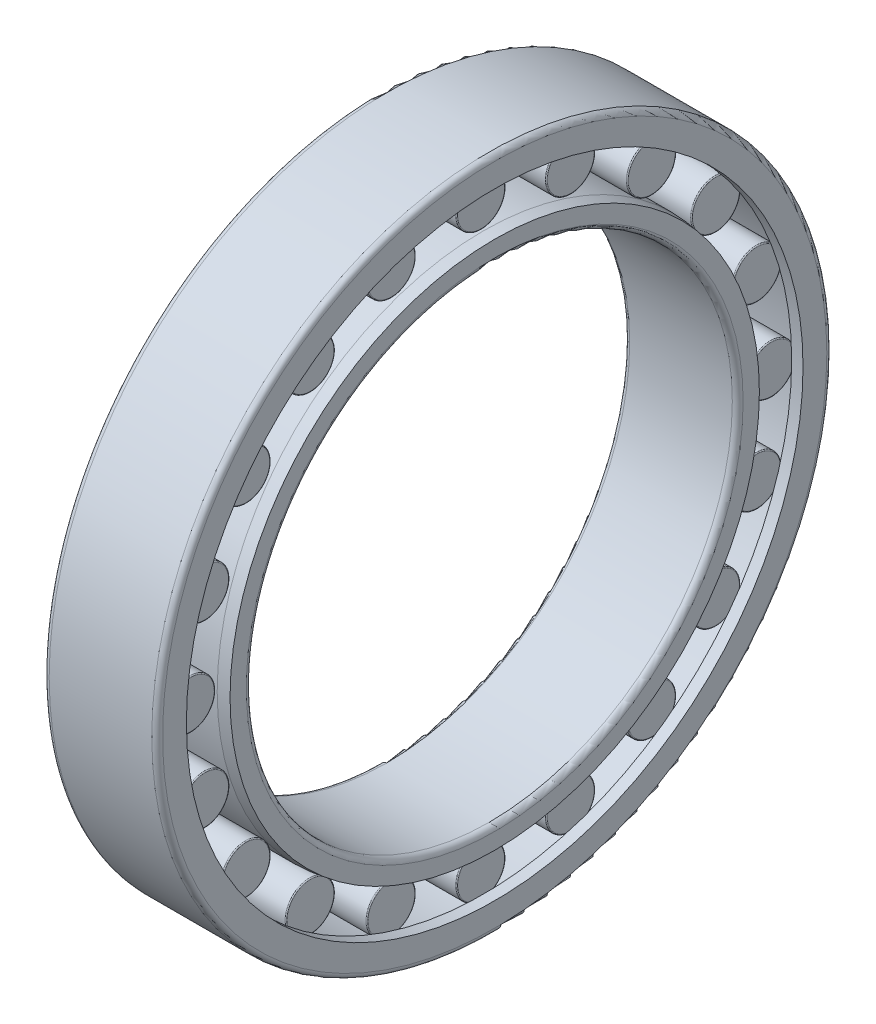
SolidWorks part; units mm, degrees
ref_plane "Plane1" through (0, 0, 0) normal (0, 0, 1) x (1, 0, 0)
ref_plane "Plane2" through (0, 0, 0) normal (0, 1, 0) x (1, 0, 0)
ref_plane "Plane3" through (0, 0, 0) normal (1, 0, 0) x (0, 0, -1)
sketch "Clipboard" plane through (0, 0, 0) normal (0, 0, 1) x (1, 0, 0)
  line L0 (-10, 0) -> (10, 0) construction
  line L1 (0, 0) -> (185.2698, -67.4327)
  line L2 (0, 0) -> (101.017, 36.7672)
  line L3 (0, 0) -> (218.798, -79.636)
  line L4 (0, 0) -> (-22.3471, -0.7804)
  dimension "CLdia" = 107.5
  dimension "Count" = 20
  dimension "Show_count" = 20
  dimension "Max_count" = 20
  dimension "Min_count" = 2
  dimension "Race_OD" = 232.84
  dimension "Race_ID" = 197.16
sketch "OutRacSke" plane through (0, 0, 0) normal (0, 0, 1) x (1, 0, 0)
  line L0 (-16.8, 114.1887) -> (-21, 114.1887)
  line L1 (-21, 114.1887) -> (-21, 123)
  line L2 (-19, 125) -> (19, 125)
  line L3 (21, 123) -> (21, 114.1888)
  line L4 (21, 114.1888) -> (16.8, 114.1888)
  line L5 (16.8, 114.1888) -> (16.8, 116.42)
  line L6 (16.8, 116.42) -> (-16.8, 116.42)
  line L7 (-16.8, 116.42) -> (-16.8, 114.1887)
  line L8 (-90, 0) -> (90, 0) construction
  arc A0 (-21, 123) -> (-19, 125) centre (-19, 123) cw
  arc A1 (19, 125) -> (21, 123) centre (19, 123) cw
  dimension "Race_OD" = 232.84
  dimension "radius" = 2
  dimension "OD" = 250
  dimension "Cyl_Len" = 33.6
  dimension "halfCylLen" = 16.8
  dimension "Width" = 42
  dimension "halfWidth" = 21
  dimension "groove_dp" = 2.2313
revolve "OuterRace" add sketch "OutRacSke" angle 360 about L8
sketch "RolDetSke" plane through (0, 0, 0) normal (0, 0, 1) x (1, 0, 0)
  line L0 (-15.96, 116.1851) -> (-15.96, 107.5)
  line L1 (-15.96, 107.5) -> (15.96, 107.5)
  line L2 (15.96, 107.5) -> (15.96, 116.1851)
  line L3 (15.5981, 116.547) -> (-15.5981, 116.547)
  line L4 (-33.6, 107.5) -> (33.6, 107.5) construction
  arc A0 (15.96, 116.1851) -> (15.5981, 116.547) centre (15.5981, 116.1851) ccw
  arc A1 (-15.5981, 116.547) -> (-15.96, 116.1851) centre (-15.5981, 116.1851) ccw
  dimension "radius" = 0.3619
  dimension "RolCLRad" = 107.5
  dimension "Length" = 31.92
  dimension "halfLength" = 15.96
  dimension "Roller_diameter" = 18.094
revolve "RollerDetailed" add sketch "RolDetSke" angle 360 about L4
ref_axis "Axis1" through (-50, 0, 0) along (1, 0, 0)
sketch "RolSimSke" plane through (0, 101.6, 0) normal (0, 0, 1) x (1, 0, 0)
  line L0 (-15.96, 14.5851) -> (-15.96, -2.7851)
  line L1 (25.4, -101.6) -> (-25.4, -101.6) construction
  line L2 (15.96, -2.7851) -> (15.96, 14.5851)
  line L3 (15.5981, 14.947) -> (-15.5981, 14.947)
  line L5 (15.5981, -3.147) -> (-15.5981, -3.147)
  arc A0 (15.96, 14.5851) -> (15.5981, 14.947) centre (15.5981, 14.5851) ccw
  arc A1 (-15.5981, 14.947) -> (-15.96, 14.5851) centre (-15.5981, 14.5851) ccw
  arc A2 (15.96, -2.7851) -> (15.5981, -3.147) centre (15.5981, -2.7851) cw
  arc A3 (-15.5981, -3.147) -> (-15.96, -2.7851) centre (-15.5981, -2.7851) cw
  dimension "radius" = 0.3619
  dimension "halfLength" = 15.96
  dimension "Roller_diameter" = 18.094
  dimension "D1" = 98.453
  dimension "Rol_Length" = 31.92
revolve "RollersSimplified" [suppressed] add sketch "RolSimSke" angle 360 about L1
sketch "InsRacSke" plane through (0, 0, 0) normal (0, 0, 1) x (1, 0, 0)
  line L0 (-16.8, 98.58) -> (-21, 98.0222)
  line L1 (-21, 98.0222) -> (-21, 92)
  line L2 (-19, 90) -> (19, 90)
  line L3 (21, 92) -> (21, 98.0222)
  line L4 (21, 98.0222) -> (16.8, 98.58)
  line L5 (16.8, 98.58) -> (-16.8, 98.58)
  line L6 (-90, 0) -> (90, 0) construction
  arc A0 (-21, 92) -> (-19, 90) centre (-19, 92) ccw
  arc A1 (19, 90) -> (21, 92) centre (19, 92) ccw
  dimension "Race_ID" = 197.16
  dimension "radius" = 2
  dimension "Cyl_Len" = 33.6
  dimension "halfWidth" = 21
  dimension "Bore" = 180
  dimension "Width" = 42
  dimension "groove_dp" = 0.5578
revolve "InnerRace" add sketch "InsRacSke" angle 360 about L6
pattern_circular "RollersDetailed" count 20 every 18 about axis through (-50, 0, 0) along (1, 0, 0) of "RollerDetailed"
sketch "CagSpiSke" plane through (0, 0, 0) normal (0, 0, 1) x (1, 0, 0)
  line L0 (18.9, 105.2383) -> (18.9, 109.7618)
  line L1 (18.9, 109.7618) -> (-18.9, 109.7618)
  line L2 (-18.9, 109.7618) -> (-18.9, 105.2383)
  line L3 (-18.9, 105.2383) -> (18.9, 105.2383)
  line L4 (-90, 0) -> (90, 0) construction
  dimension "Cag_IR" = 210.4765
  dimension "thickness" = 4.5235
  dimension "width" = 37.8
  dimension "halfwidth" = 18.9
revolve "CageSpine" [suppressed] add sketch "CagSpiSke" angle 360 about L4
equation "\"CLdia@Clipboard\" =  ( \"Race_OD@Clipboard\" + \"Race_ID@Clipboard\" )  / 4"
equation "\"Race_OD@OutRacSke\" = \"Race_OD@Clipboard\""
equation "\"halfCylLen@OutRacSke\" = \"Cyl_Len@OutRacSke\" / 2"
equation "\"RolCLRad@RolDetSke\" = \"CLdia@Clipboard\""
equation "\"Roller_diameter@RolDetSke\" =  ( \"Race_OD@Clipboard\" - \"Race_ID@Clipboard\" )  / 2 + .01"
equation "\"Roller_diameter@RolSimSke\" =  ( \"Race_OD@Clipboard\" - \"Race_ID@Clipboard\" )  / 2 + .01"
equation "\"radius@RolDetSke\" = \"Roller_diameter@RolDetSke\" / 50"
equation "\"Length@RolDetSke\" = \"Cyl_Len@OutRacSke\" * .95"
equation "\"halfLength@RolDetSke\" = \"Length@RolDetSke\" / 2"
equation "\"thickness@CagSpiSke\"  = \"Roller_diameter@RolDetSke\" * .25"
equation "\"Cag_IR@CagSpiSke\" =  \"RolCLRad@RolDetSke\" * 2 - \"thickness@CagSpiSke\""
equation "\"Rol_Length@RolSimSke\" = \"Cyl_Len@InsRacSke\" * .95"
equation "\"halfLength@RolSimSke\" = \"Rol_Length@RolSimSke\" / 2"
equation "\"radius@RolSimSke\" = \"radius@RolDetSke\""
equation "\"D1@RolSimSke\" = \"CLdia@Clipboard\" -  ( \"Roller_diameter@RolSimSke\" / 2 ) "
equation "\"Max_count@Clipboard\" = int( 3.14159265 / atn(( \"Roller_diameter@RolDetSke\" / 2) / sqr( \"RolCLRad@RolDetSke\"  *  \"RolCLRad@RolDetSke\" - ( \"Roller_diameter@RolDetSke\" / 2) *  ( \"Roller_diameter@RolDetSke\" / 2))))"
equation "\"Max_count@Clipboard\" = ((sgn( \"Max_count@Clipboard\" - \"Count@Clipboard\" )-1)*( \"Max_count@Clipboard\" - \"Count@Clipboard\" ))/-2+ \"Count@Clipboard\""
equation "\"Count@RollersDetailed\" = int( \"Show_count@Clipboard\" ) "
equation "\"Count@RollersDetailed\" = ((sgn( \"Count@RollersDetailed\" - \"Max_count@Clipboard\" )-1)*( \"Count@RollersDetailed\" - \"Max_count@Clipboard\" ))/-2+ \"Max_count@Clipboard\""
equation "\"Count@RollersDetailed\" = ((sgn( \"Count@RollersDetailed\" - \"Min_count@Clipboard\" )+1)*( \"Count@RollersDetailed\" - \"Min_count@Clipboard\"))/2 +\"Min_count@Clipboard\""
equation "\"Angle@RollersDetailed\" = 360.0 / \"Max_count@Clipboard\""
equation "\"radius@InsRacSke\" = \"radius@OutRacSke\""
equation "\"groove_dp@InsRacSke\" = \"groove_dp@OutRacSke\" / 4"
equation "\"Width@InsRacSke\" = \"Width@OutRacSke\""
equation "\"halfWidth@OutRacSke\" = \"Width@OutRacSke\" / 2"
equation "\"halfWidth@InsRacSke\" = \"Width@InsRacSke\" / 2"
equation "\"Race_ID@InsRacSke\" = \"Race_ID@Clipboard\""
equation "\"Cyl_Len@InsRacSke\" = \"Cyl_Len@OutRacSke\""
equation "\"Angle@CageSpine\" =  \"Angle@RollersDetailed\" * ( \"Count@RollersDetailed\" -1 + int( \"Count@RollersDetailed\" / \"Max_count@Clipboard\" ) )  + 0.001 -  int( \"Count@RollersDetailed\" / \"Max_count@Clipboard\" ) * 0.001"
equation "\"Angle@CageSpine\" =  \"Angle@CageSpine\" * int( \"Min_count@Clipboard\" / 2) + int(1 / \"Min_count@Clipboard\")  * 0.001"
equation "\"width@CagSpiSke\" =   ( \"Width@InsRacSke\" + \"Cyl_Len@InsRacSke\" )  / 2"
equation "\"halfwidth@CagSpiSke\" = \"width@CagSpiSke\" / 2"
